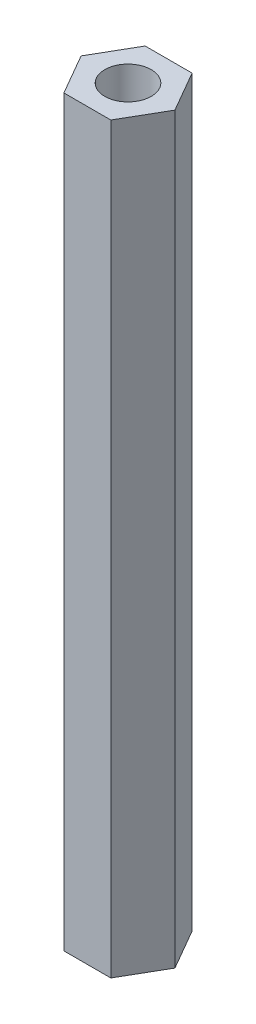
SolidWorks part; units mm, degrees
ref_plane "Front Plane" through (0, 0, 0) normal (0, 0, 1) x (1, 0, 0)
ref_plane "Top Plane" through (0, 0, 0) normal (0, 1, 0) x (1, 0, 0)
ref_plane "Right Plane" through (0, 0, 0) normal (1, 0, 0) x (0, 0, -1)
sketch "Sketch1" plane through (0, 0, 0) normal (0, 1, 0) x (1, 0, 0)
  line L1 (2.0207, 3.5) -> (-2.0207, 3.5)
  line L2 (-2.0207, 3.5) -> (-4.0415, 0)
  line L3 (-4.0415, 0) -> (-2.0207, -3.5)
  line L4 (-2.0207, -3.5) -> (2.0207, -3.5)
  line L5 (2.0207, -3.5) -> (4.0415, 0)
  line L6 (4.0415, 0) -> (2.0207, 3.5)
  circle A0 centre (0, 0) radius 3.5 construction
  circle A1 centre (0, 0) radius 2
  dimension "D1" = 7
  dimension "D2" = 4
extrude "Boss-Extrude1" add sketch "Sketch1" along normal blind 64
